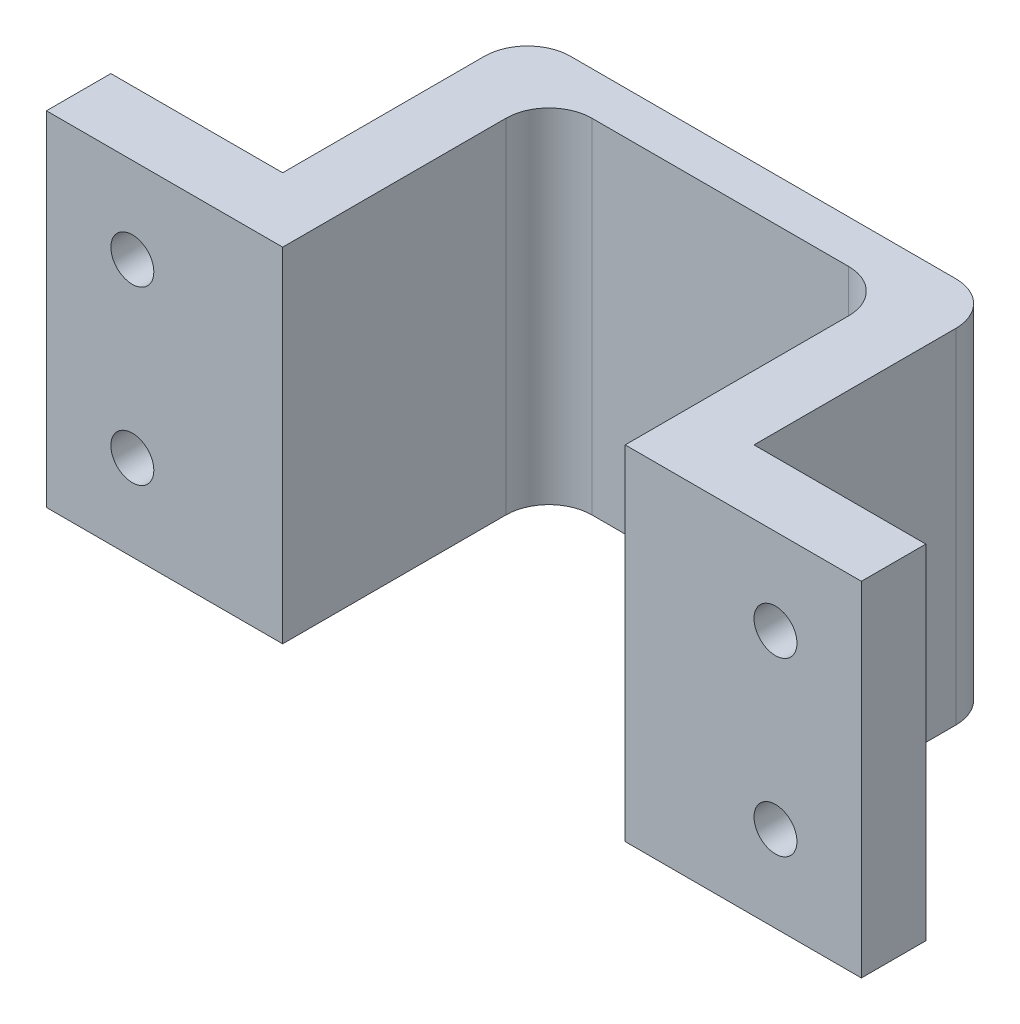
SolidWorks part; units mm, degrees
ref_plane "Front" through (0, 0, 0) normal (0, 0, 1) x (1, 0, 0)
ref_plane "Top" through (0, 0, 0) normal (0, 1, 0) x (1, 0, 0)
ref_plane "Right" through (0, 0, 0) normal (1, 0, 0) x (0, 0, -1)
sketch "Sketch1" plane through (0, 0, 0) normal (0, 0, 1) x (1, 0, 0)
  line L1 (0, 0) -> (21.95, 0)
  line L2 (0, 0) -> (0, 16)
  line L3 (0, 16) -> (21.95, 16)
  line L4 (21.95, 0) -> (21.95, 16)
  dimension "D1" = 21.95
  dimension "D2" = 16
extrude "Boss-Extrude1" add sketch "Sketch1" along normal blind 2
sketch "Sketch2" plane through (0, 0, 2) normal (0, 0, 1) x (1, 0, 0)
  line L0 (0, 0) -> (21.95, 0) construction
  line L1 (0, 16) -> (3, 16)
  line L2 (0, 16) -> (0, 0)
  line L3 (0, 0) -> (3, 0)
  line L4 (3, 16) -> (3, 0)
  line L6 (21.95, 16) -> (18.95, 16)
  line L7 (21.95, 16) -> (21.95, 0)
  line L8 (21.95, 0) -> (18.95, 0)
  line L9 (18.95, 16) -> (18.95, 0)
  dimension "D1" = 3
  dimension "D2" = 3
extrude "Boss-Extrude2" add sketch "Sketch2" along normal blind 12.4
sketch "Sketch3" plane through (21.95, 0, 0) normal (1, 0, 0) x (0, 0, -1)
  line L0 (-14.4, 0) -> (0, 0) construction
  line L1 (-14.4, 16) -> (-11.4, 16)
  line L2 (-14.4, 16) -> (-14.4, 0)
  line L3 (-14.4, 0) -> (-11.4, 0)
  line L4 (-11.4, 16) -> (-11.4, 0)
  dimension "D1" = 3
extrude "Boss-Extrude3" add sketch "Sketch3" along normal blind 8
sketch "Sketch4" plane through (0, 0, 0) normal (-1, 0, 0) x (0, 0, 1)
  line L0 (14.4, 16) -> (0, 16) construction
  line L1 (14.4, 0) -> (11.4, 0)
  line L2 (14.4, 0) -> (14.4, 16)
  line L3 (14.4, 16) -> (11.4, 16)
  line L4 (11.4, 0) -> (11.4, 16)
  dimension "D1" = 3
extrude "Boss-Extrude4" add sketch "Sketch4" along normal blind 8
sketch "Sketch5" plane through (0, 0, 11.4) normal (0, 0, -1) x (-1, 0, 0)
  line L0 (-29.95, 0) -> (-29.95, 16) construction
  line L1 (-29.95, 0) -> (-21.95, 0) construction
  line L2 (8, 0) -> (0, 0) construction
  line L3 (8, 16) -> (8, 0) construction
  line L4 (8, 16) -> (0, 16) construction
  line L5 (-29.95, 16) -> (-21.95, 16) construction
  circle A0 centre (4, 4) radius 1
  circle A1 centre (-25.95, 4) radius 1
  circle A2 centre (4, 12) radius 1
  circle A3 centre (-25.95, 12) radius 1
  dimension "D5" = 2
  dimension "D6" = 2
  dimension "D7" = 2
  dimension "D8" = 2
  dimension "D1" = 4
  dimension "D2" = 4
  dimension "D3" = 4
  dimension "D4" = 4
  dimension "D9" = 4
  dimension "D10" = 4
  dimension "D11" = 4
  dimension "D12" = 4
extrude "Cut-Extrude1" cut sketch "Sketch5" against normal blind 8
fillet "Fillet1" radius 2 2 edges at (3, 8, 2) (18.95, 8, 2)
fillet "Fillet2" radius 2 2 edges at (0, 8, 0) (21.95, 8, 0)
